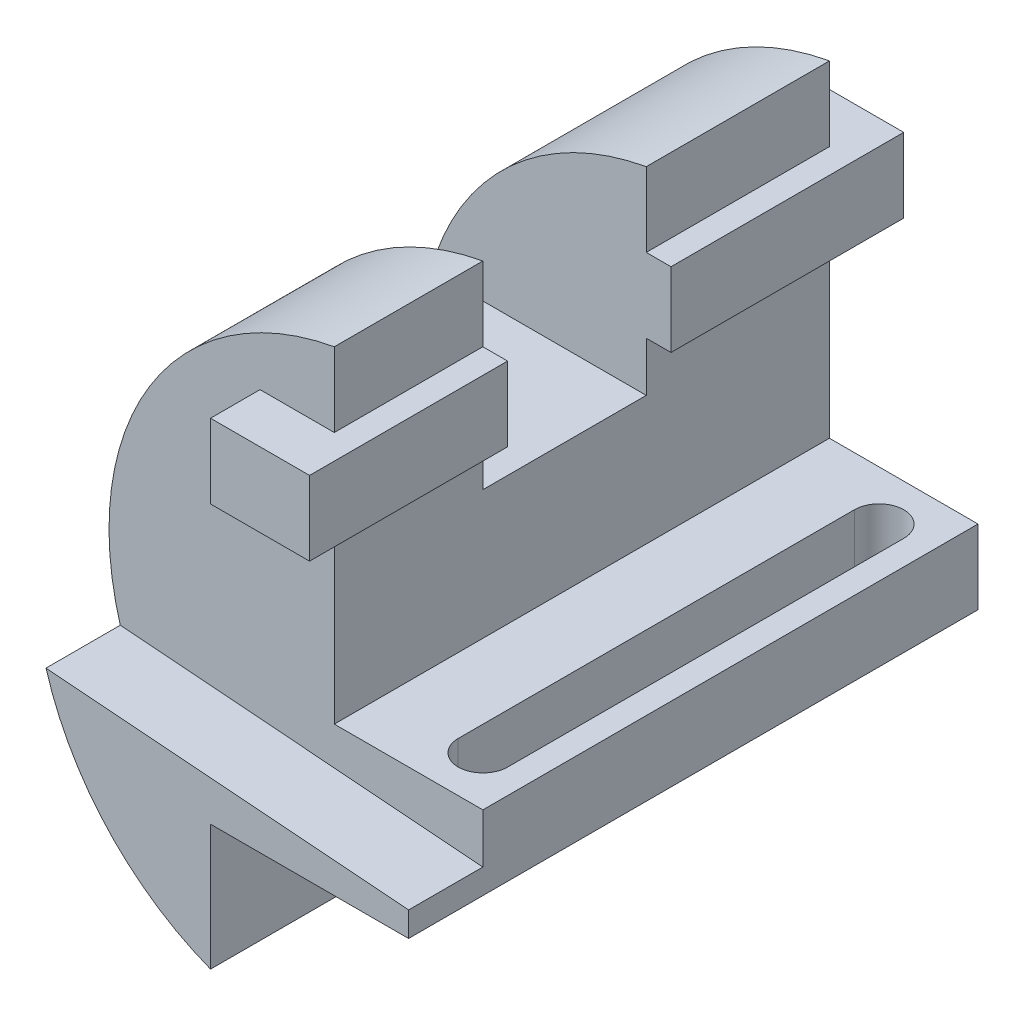
SolidWorks part; units mm, degrees
material "1060 Alloy"
ref_plane "Front Plane" through (0, 0, 0) normal (0, 0, 1) x (1, 0, 0)
ref_plane "Top Plane" through (0, 0, 0) normal (0, 1, 0) x (1, 0, 0)
ref_plane "Right Plane" through (0, 0, 0) normal (1, 0, 0) x (0, 0, -1)
sketch "Sketch1" plane through (0, 0, 0) normal (0, 0, 1) x (1, 0, 0)
  line L0 (0, 0) -> (-40, 0)
  line L1 (-40, 0) -> (-40, -25.3628)
  line L2 (0, 0) -> (0, 15)
  line L3 (0, 15) -> (-30, 15)
  line L4 (-30, 15) -> (-30, 81)
  arc A0 (-40, -25.3628) -> (-30, 81) centre (-20, 26.4083) cw
  dimension "D5" = 55.5
  dimension "D1" = 15
  dimension "D2" = 40
  dimension "D3" = 30
  dimension "D4" = 10
  dimension "D6" = 66
extrude "Boss-Extrude1" add sketch "Sketch1" along normal blind 115
sketch "Sketch2" plane through (0, 0, 115) normal (0, 0, 1) x (1, 0, 0)
  line L0 (0, 5) -> (-73.2264, 10.6857)
  line L2 (0, 0) -> (0, 15) construction
  line L12 (0, 0) -> (0, 15)
  line L13 (0, 15) -> (-30, 15)
  line L14 (-30, 15) -> (-30, 81)
  line L15 (-40, -25.3628) -> (-40, 0)
  line L16 (-40, 0) -> (0, 0)
  line L17 (0, 5) -> (0, 15)
  line L18 (0, 15) -> (-30, 15)
  line L19 (-30, 15) -> (-30, 81)
  arc A2 (-30, 81) -> (-40, -25.3628) centre (-20, 26.4083) ccw
  arc A3 (-30, 81) -> (-73.2264, 10.6857) centre (-20, 26.4083) ccw
  point P5 (0, 0)
  dimension "D1" = 85.56
  dimension "D2" = 5
  dimension "D3" = 0
extrude "Cut-Extrude1" cut sketch "Sketch2" against normal blind 15
sketch "Sketch3" plane through (0, 0, 0) normal (0, 0, -1) x (-1, 0, 0)
  line L0 (30, 15) -> (30, 81) construction
  line L1 (25, 66) -> (45, 66)
  line L2 (25, 66) -> (25, 51)
  line L3 (25, 51) -> (45, 51)
  line L4 (45, 66) -> (45, 51)
  dimension "D1" = 5
  dimension "D2" = 20
  dimension "D3" = 15
  dimension "D4" = 15
extrude "Boss-Extrude2" add sketch "Sketch3" against normal offset from surface 5 and the other way blind 10 up to face at (-31.4845, -2.7089, 115)
sketch "Sketch4" plane through (-30, 0, 0) normal (1, 0, 0) x (0, 0, -1)
  line L0 (-100, 81) -> (0, 81) construction
  line L1 (-70, 81) -> (-37, 81)
  line L2 (-70, 81) -> (-70, 41)
  line L3 (-70, 41) -> (-37, 41)
  line L4 (-37, 81) -> (-37, 41)
  line L5 (-100, 51) -> (0, 51) construction
  dimension "D1" = 33
  dimension "D2" = 30
  dimension "D3" = 33
  dimension "D4" = 10
extrude "Cut-Extrude2" cut sketch "Sketch4" against normal through all both and the other way through all
sketch "Sketch5" plane through (0, 15, 0) normal (0, 1, 0) x (1, 0, 0)
  line L0 (-9.9803, -10) -> (-9.9803, -90) construction
  line L1 (-4.9803, -10) -> (-4.9803, -90)
  line L2 (-14.9803, -10) -> (-14.9803, -90)
  line L3 (0, -100) -> (0, 0) construction
  line L4 (0, -100) -> (-30, -100) construction
  arc A0 (-4.9803, -10) -> (-14.9803, -10) centre (-9.9803, -10) ccw
  arc A1 (-14.9803, -90) -> (-4.9803, -90) centre (-9.9803, -90) ccw
  point P2 (-9.9803, -50)
  dimension "D1" = 80
  dimension "D2" = 10
  dimension "D3" = 9.9803
  dimension "D4" = 10
extrude "Cut-Extrude3" cut sketch "Sketch5" against normal through all both and the other way through all
equation "\"a\"= 55.5mm"
equation "\"b\"= 66mm"
equation "\"c\"= 33mm"
equation "\"D5@Sketch1\"=\"a\""
